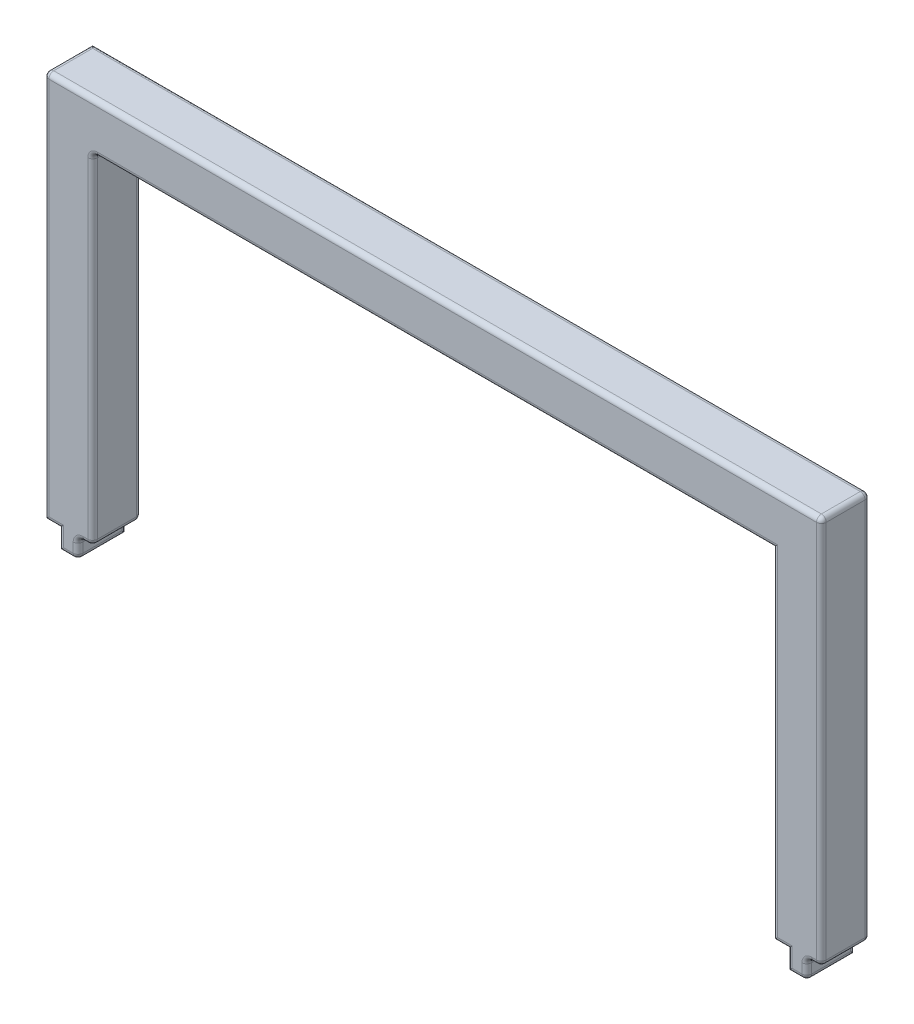
SolidWorks part; units mm, degrees
ref_plane "Front Plane" through (0, 0, 0) normal (0, 0, 1) x (1, 0, 0)
ref_plane "Top Plane" through (0, 0, 0) normal (0, 1, 0) x (1, 0, 0)
ref_plane "Right Plane" through (0, 0, 0) normal (1, 0, 0) x (0, 0, -1)
sketch "Sketch1" plane through (0, 0, 0) normal (0, 0, 1) x (1, 0, 0)
  line L1 (185.6338, -112.8662) -> (265.6338, -112.8662)
  line L2 (185.6338, -112.8662) -> (185.6338, -152.8662)
  line L3 (185.6338, -152.8662) -> (265.6338, -152.8662)
  line L4 (265.6338, -112.8662) -> (265.6338, -152.8662)
  line L5 (187.1338, -152.8662) -> (189.1338, -152.8662)
  line L6 (187.1338, -152.8662) -> (187.1338, -154.8662)
  line L7 (187.1338, -154.8662) -> (189.1338, -154.8662)
  line L8 (189.1338, -152.8662) -> (189.1338, -154.8662)
  line L9 (262.1338, -152.8662) -> (264.1338, -152.8662)
  line L10 (262.1338, -152.8662) -> (262.1338, -154.8662)
  line L11 (262.1338, -154.8662) -> (264.1338, -154.8662)
  line L12 (264.1338, -152.8662) -> (264.1338, -154.8662)
  line L13 (190.6338, -152.8662) -> (260.6338, -152.8662)
  line L14 (190.6338, -152.8662) -> (190.6338, -117.8662)
  line L15 (190.6338, -117.8662) -> (260.6338, -117.8662)
  line L16 (260.6338, -152.8662) -> (260.6338, -117.8662)
  dimension "D1" = 80
  dimension "D2" = 40
  dimension "D3" = 5
  dimension "D4" = 5
  dimension "D5" = 5
  dimension "D6" = 2
  dimension "D7" = 2
  dimension "D8" = 2
  dimension "D9" = 2
  dimension "D10" = 1.5
  dimension "D11" = 1.5
extrude "Boss-Extrude1" add sketch "Sketch1" along normal blind 5 contours L16 L3 L4 L1 L2 L14 L15 | L8 L3 L6 L7 | L12 L3 L10 L11
fillet "Fillet1" radius 0.5 33 edges at (264.8838, -152.8662, 0) (189.8838, -152.8662, 0) (225.6338, -117.8662, 0) (264.1338, -153.8662, 0) (265.6338, -132.8662, 0) (225.6338, -112.8662, 0) (189.1338, -153.8662, 0) (190.6338, -135.3662, 0) (260.6338, -135.3662, 5) (261.3838, -152.8662, 5) (262.1338, -153.8662, 5) (263.1338, -154.8662, 5) (264.1338, -153.8662, 5) (264.8838, -152.8662, 5) (265.6338, -132.8662, 5) (225.6338, -112.8662, 5) (185.6338, -132.8662, 5) (186.3838, -152.8662, 5) (187.1338, -153.8662, 5) (188.1338, -154.8662, 5) (189.1338, -153.8662, 5) (189.8838, -152.8662, 5) (190.6338, -135.3662, 5) (225.6338, -117.8662, 5) (190.6338, -117.8662, 2.5) (190.6338, -152.8662, 2.5) (189.1338, -152.8662, 2.5) (189.1338, -154.8662, 2.5) (185.6338, -112.8662, 2.5) (265.6338, -112.8662, 2.5) (265.6338, -152.8662, 2.5) (264.1338, -152.8662, 2.5) (264.1338, -154.8662, 2.5)
equation "\"ScannerWidth\" = 80"
equation "\"ScannerHeight\" = 40"
equation "\"ScannerThickness\" = 5"
equation "\"LegWidth\" = 2"
equation "\"LegDepth\" = 2"
equation "\"D1@Sketch1\"=\"ScannerWidth\""
equation "\"D2@Sketch1\"=\"ScannerHeight\""
equation "\"D3@Sketch1\"=\"ScannerThickness\""
equation "\"D4@Sketch1\"=\"ScannerThickness\""
equation "\"D5@Sketch1\"=\"ScannerThickness\""
equation "\"D6@Sketch1\"=\"LegWidth\""
equation "\"D7@Sketch1\"=\"LegDepth\""
equation "\"D8@Sketch1\"=\"LegDepth\""
equation "\"D9@Sketch1\"=\"LegDepth\""
equation "\"D10@Sketch1\"=(\"ScannerThickness\"-\"LegWidth\")/2"
equation "\"D11@Sketch1\"=(\"ScannerThickness\"-\"LegWidth\")/2"
equation "\"ScannerDepth\" = 5"
equation "\"D1@Boss-Extrude1\"=\"ScannerDepth\""
